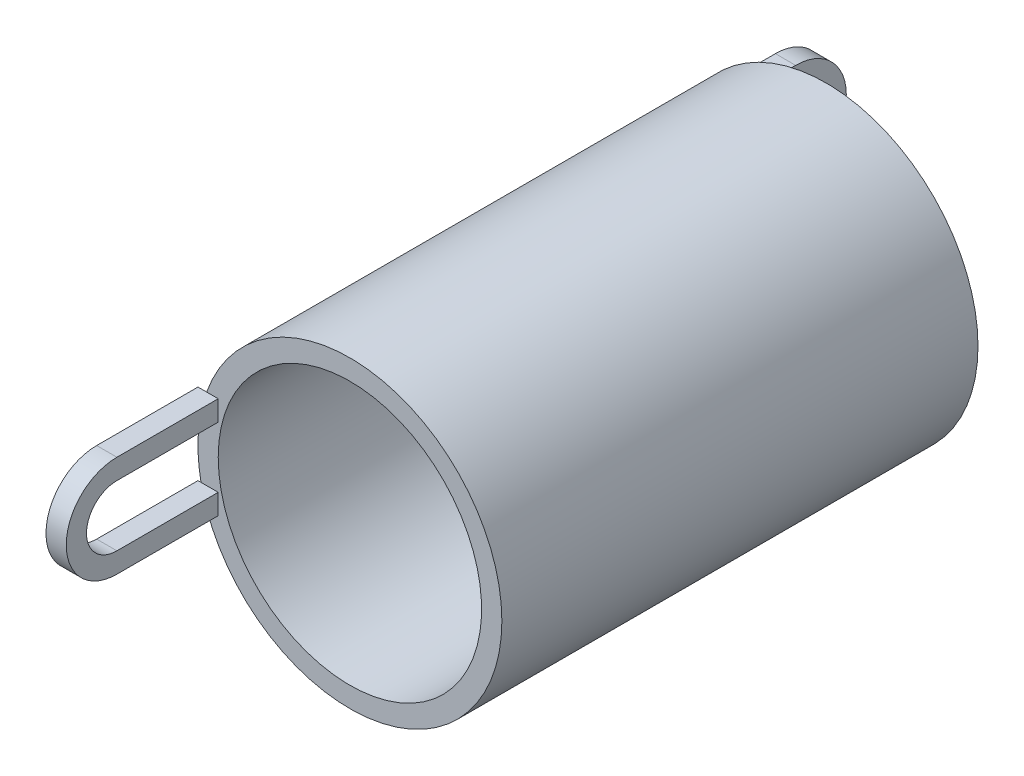
SolidWorks part; units mm, degrees
ref_plane "Plano frontal" through (0, 0, 0) normal (0, 0, 1) x (1, 0, 0)
ref_plane "Plano superior" through (0, 0, 0) normal (0, 1, 0) x (1, 0, 0)
ref_plane "Plano direito" through (0, 0, 0) normal (1, 0, 0) x (0, 0, -1)
sketch "Esboço2" plane through (0, 0, 0) normal (0, 0, 1) x (1, 0, 0)
  circle A0 centre (0, 0) radius 7.5
  circle A1 centre (0, 0) radius 6.5
  point P4 (6.5, 0)
  point P5 (7.5, 0)
  dimension "D2" = 15
  dimension "D1" = 1
extrude "Ressalto-extrusão1" add sketch "Esboço2" along normal blind 23.5
ref_plane "Plano1" through (-7.5, 0, 0) normal (-1, 0, 0) x (0, 0, 1)
sketch "Esboço3" plane through (-7.5, 0, 0) normal (1, 0, 0) x (0, 0, -1)
  line L0 (5, 1.5) -> (0, 1.5)
  line L1 (5, 2.5) -> (0, 2.5)
  line L2 (0, 2.5) -> (0, 1.5)
  line L3 (0, -7.5) -> (0, 7.5) construction
  line L4 (5, 0) -> (0, 0) construction
  line L5 (5, -2.5) -> (0, -2.5)
  line L6 (5, -1.5) -> (0, -1.5)
  line L7 (0, 0) -> (-23.5, 0) construction
  line L8 (-23.5, 7.5) -> (-23.5, -7.5) construction
  line L9 (-11.75, 0) -> (-11.75, 7.5) construction
  line L10 (0, 7.5) -> (-23.5, 7.5) construction
  line L11 (-28.5, 2.5) -> (-23.5, 2.5)
  line L12 (-28.5, 1.5) -> (-23.5, 1.5)
  line L13 (-28.5, -1.5) -> (-23.5, -1.5)
  line L14 (-28.5, -2.5) -> (-23.5, -2.5)
  line L15 (0, -2.5) -> (0, -1.5)
  line L16 (-23.5, -2.5) -> (-23.5, -1.5)
  line L17 (-23.5, 1.5) -> (-23.5, 2.5)
  arc A0 (5, -2.5) -> (5, 2.5) centre (5, 0) ccw
  arc A1 (5, -1.5) -> (5, 1.5) centre (5, 0) ccw
  arc A2 (-28.5, -1.5) -> (-28.5, 1.5) centre (-28.5, 0) cw
  arc A3 (-28.5, -2.5) -> (-28.5, 2.5) centre (-28.5, 0) cw
  dimension "D1" = 3
  dimension "D2" = 1
  dimension "D3" = 5
extrude "Ressalto-extrusão2" add sketch "Esboço3" along normal blind 1
